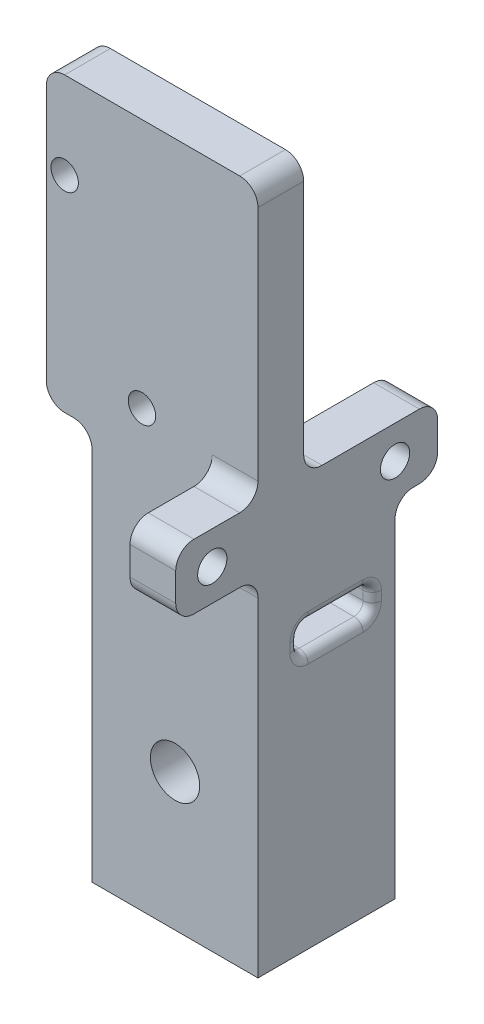
SolidWorks part; units mm, degrees
ref_plane "Front Plane" through (0, 0, 0) normal (0, 0, 1) x (1, 0, 0)
ref_plane "Top Plane" through (0, 0, 0) normal (0, 1, 0) x (1, 0, 0)
ref_plane "Right Plane" through (0, 0, 0) normal (1, 0, 0) x (0, 0, -1)
sketch "Sketch1" plane through (0, 0, 0) normal (0, 0, 1) x (1, 0, 0)
  line L0 (0, -10.4775) -> (0, 10.4775) construction
  line L1 (-11.5282, -47.625) -> (11.5282, -47.625)
  line L2 (-11.5282, -47.625) -> (-11.5282, 47.625)
  line L3 (-11.5282, 47.625) -> (11.5282, 47.625)
  line L4 (11.5282, -47.625) -> (11.5282, 47.625)
  line L5 (-11.5282, -47.625) -> (11.5282, 47.625) construction
  line L6 (-11.5282, 47.625) -> (11.5282, -47.625) construction
  line L7 (-7.9121, 16.6878) -> (7.9121, 16.6878)
  line L8 (-7.9121, 16.6878) -> (-7.9121, 44.45)
  line L9 (-7.9121, 44.45) -> (7.9121, 44.45)
  line L10 (7.9121, 16.6878) -> (7.9121, 44.45)
  line L11 (-7.9121, 16.6878) -> (7.9121, 44.45) construction
  line L12 (-7.9121, 44.45) -> (7.9121, 16.6878) construction
  circle A0 centre (-5.3721, 41.91) radius 1.27
  circle A1 centre (5.3721, 19.2278) radius 1.27
  point P0 (0, 0)
  point P6 (0, 30.5689)
  dimension "D4" = 2.54
  dimension "D5" = 2.54
  dimension "D6" = 2.54
  dimension "D7" = 2.54
  dimension "D8" = 2.54
  dimension "D1" = 95.25
  dimension "D2" = 27.7622
  dimension "D3" = 15.8242
  dimension ".1" = 2.54
  dimension "D9" = 3.175
extrude "Boss-Extrude1" add sketch "Sketch1" along normal blind 6.35 contours L1 L4 L3 L2 L10 L7 L8 L9 | L7 L10 L9 L8 A1 A0 | A0 | A1
sketch "Sketch2" plane through (0, 0, 0) normal (0, 0, -1) x (-1, 0, 0)
  line L0 (11.5282, -47.625) -> (11.5282, 47.625) construction
  line L1 (-11.5282, -47.625) -> (11.5282, -47.625)
  line L2 (-11.5282, -47.625) -> (-11.5282, 0.635)
  line L3 (-11.5282, 0.635) -> (11.5282, 0.635)
  line L4 (11.5282, -47.625) -> (11.5282, 0.635)
  dimension "D1" = 48.26
extrude "Boss-Extrude2" add sketch "Sketch2" along normal blind 12.7
sketch "Sketch5" plane through (11.5282, 0, 0) normal (1, 0, 0) x (0, 0, -1)
  line L0 (12.7, 0.635) -> (0, 0.635) construction
  line L1 (-0.635, -12.065) -> (9.525, -12.065)
  line L2 (-0.635, -12.065) -> (-0.635, -8.255)
  line L3 (-0.635, -8.255) -> (9.525, -8.255)
  line L4 (9.525, -12.065) -> (9.525, -8.255)
  line L5 (-0.635, -12.065) -> (9.525, -8.255) construction
  line L6 (-0.635, -8.255) -> (9.525, -12.065) construction
  line L7 (12.7, 0.635) -> (12.7, -47.625) construction
  point P0 (4.445, -10.16)
  dimension "D1" = 8.89
  dimension "D2" = 3.175
  dimension "D3" = 10.16
  dimension "D4" = 3.81
extrude "Cut-Extrude2" cut sketch "Sketch5" against normal through all
sketch "Sketch6" plane through (0, 0, -12.7) normal (0, 0, -1) x (-1, 0, 0)
  line L0 (0, 3.4925) -> (0, -3.4925) construction
  line L1 (-11.5282, -47.625) -> (11.5282, -47.625) construction
  circle A0 centre (0, -28.575) radius 3.429
  dimension "D1" = 19.05
  dimension "D2" = 6.858
extrude "Cut-Extrude3" cut sketch "Sketch6" against normal through all
fillet "Fillet2" radius 1.27 12 edges at (-11.5282, -10.16, -9.525) (-11.5282, -12.065, -4.445) (-11.5282, -10.16, 0.635) (-11.5282, -8.255, -4.445) (0, -8.255, -9.525) (0, -12.065, -9.525) (0, -8.255, 0.635) (0, -12.065, 0.635) (11.5282, -10.16, -9.525) (11.5282, -12.065, -4.445) (11.5282, -10.16, 0.635) (11.5282, -8.255, -4.445)
sketch "Sketch8" plane through (-11.5282, 0, 0) normal (-1, 0, 0) x (0, 0, 1)
  line L1 (6.35, 47.625) -> (0, 47.625)
  line L2 (6.35, 47.625) -> (6.35, 6.9863)
  line L3 (6.35, 6.9863) -> (0, 6.9863)
  line L4 (0, 47.625) -> (0, 6.9863)
  line L5 (0, -12.681) -> (0, 12.681) construction
extrude "Boss-Extrude3" add sketch "Sketch8" along normal blind 6.35
sketch "Sketch9" plane through (0, 0, 0) normal (0, 0, 1) x (1, 0, 0)
  line L0 (-17.8782, 47.625) -> (-17.8782, 6.9863) construction
  line L7 (-17.8782, 10.3378) -> (-2.054, 10.3378)
  line L8 (-17.8782, 10.3378) -> (-17.8782, 38.1)
  line L9 (-17.8782, 38.1) -> (-2.054, 38.1)
  line L10 (-2.054, 10.3378) -> (-2.054, 38.1)
  line L11 (-17.8782, 10.3378) -> (-2.054, 38.1) construction
  line L12 (-17.8782, 38.1) -> (-2.054, 10.3378) construction
  circle A0 centre (-15.3382, 35.56) radius 1.905
  circle A1 centre (-4.594, 12.8778) radius 1.905
  point P0 (0, 0)
  point P6 (-9.9661, 24.2189)
  dimension "D4" = 3.81
  dimension "D5" = 3.81
  dimension "D6" = 2.54
  dimension "D7" = 2.54
  dimension "D8" = 2.54
  dimension "D1" = 0
  dimension "D2" = 27.7622
  dimension "D3" = 15.8242
  dimension ".1" = 2.54
extrude "Cut-Extrude4" cut sketch "Sketch9" along normal through all contours A1 | A0
fillet "Fillet4" radius 2.54 4 edges at (-17.8782, 47.625, 3.175) (11.5282, 47.625, 3.175) (-11.5282, 6.9863, 3.175) (-17.8782, 6.9863, 3.175)
sketch "Sketch12" plane through (11.5282, 0, 0) normal (1, 0, 0) x (0, 0, -1)
  line L0 (-6.35, -47.625) -> (-6.35, 45.085) construction
  line L1 (-6.35, 0.635) -> (18.6137, 0.635)
  line L4 (18.6137, 0.635) -> (18.6137, 9.6272)
  line L5 (-17.782, 9.6272) -> (18.6137, 9.6272)
  line L6 (-6.35, 0.635) -> (-17.782, 0.635)
  line L9 (-17.782, 0.635) -> (-17.782, 9.6272)
extrude "Boss-Extrude7" add sketch "Sketch12" against normal blind 6.35
fillet "Fillet5" radius 2.54 5 edges at (8.3532, 0.635, -12.7) (5.1782, 5.1311, 0) (8.3532, 9.6272, 0) (8.3532, 0.635, 6.35) (8.3532, 9.6272, 6.35)
fillet "Fillet6" radius 2.54 1 edges at (5.1782, -0.635, -12.7)
sketch "Sketch13" plane through (11.5282, 0, 0) normal (1, 0, 0) x (0, 0, -1)
  circle A0 centre (-12.702, 5.0507) radius 2.032
  circle A1 centre (12.698, 5.0507) radius 2.032
  dimension "D1" = 4.064
  dimension "D2" = 4.064
  dimension "D3" = 25.4
extrude "Cut-Extrude5" cut sketch "Sketch13" against normal blind 6.35
fillet "Fillet7" radius 2.54 4 edges at (8.3532, 0.635, -18.6137) (8.3532, 9.6272, -18.6137) (8.3532, 0.635, 17.782) (8.3532, 9.6272, 17.782)
